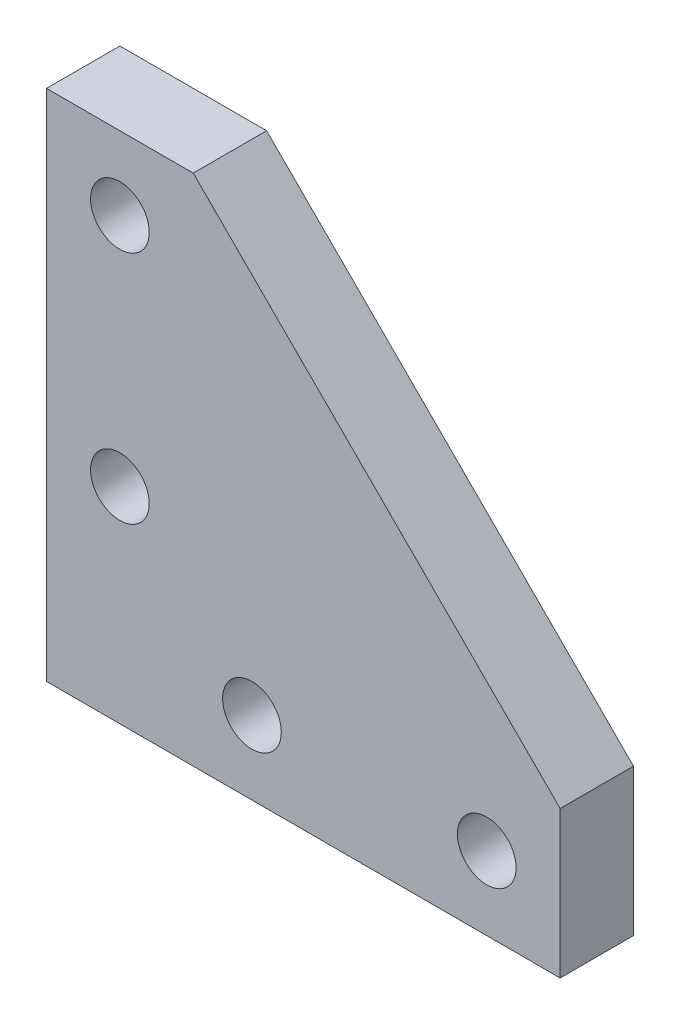
SolidWorks part; units mm, degrees
ref_plane "Plan de face" through (0, 0, 0) normal (0, 0, 1) x (1, 0, 0)
ref_plane "Plan de dessus" through (0, 0, 0) normal (0, 1, 0) x (1, 0, 0)
ref_plane "Plan de droite" through (0, 0, 0) normal (1, 0, 0) x (0, 0, -1)
sketch "Esquisse1" plane through (0, 0, 0) normal (0, 0, 1) x (1, 0, 0)
  line L0 (0, 0) -> (35, 0)
  line L1 (35, 0) -> (35, 10)
  line L2 (35, 10) -> (10, 35)
  line L3 (10, 35) -> (0, 35)
  line L4 (0, 35) -> (0, 0)
  dimension "D1" = 10
  dimension "D2" = 35
extrude "Boss.-Extru.1" add sketch "Esquisse1" along normal blind 5
sketch "Esquisse2" plane through (0, 0, 5) normal (0, 0, 1) x (1, 0, 0)
  line L0 (5, 35) -> (5, 0) construction
  line L1 (10, 35) -> (0, 35) construction
  line L2 (0, 0) -> (35, 0) construction
  line L3 (35, 5) -> (0, 5) construction
  line L4 (35, 0) -> (35, 10) construction
  line L5 (0, 35) -> (0, 0) construction
  circle A0 centre (14, 5) radius 2
  circle A1 centre (30, 5) radius 2
  circle A2 centre (5, 30) radius 2
  circle A3 centre (5, 14) radius 2
  dimension "D1" = 4
  dimension "D3" = 5
  dimension "D2" = 5
  dimension "D4" = 16
  dimension "D5" = 16
extrude "Enlèv. mat.-Extru.1" cut sketch "Esquisse2" against normal up to vertex (5 mm away) up to point (35, 10, 0)
